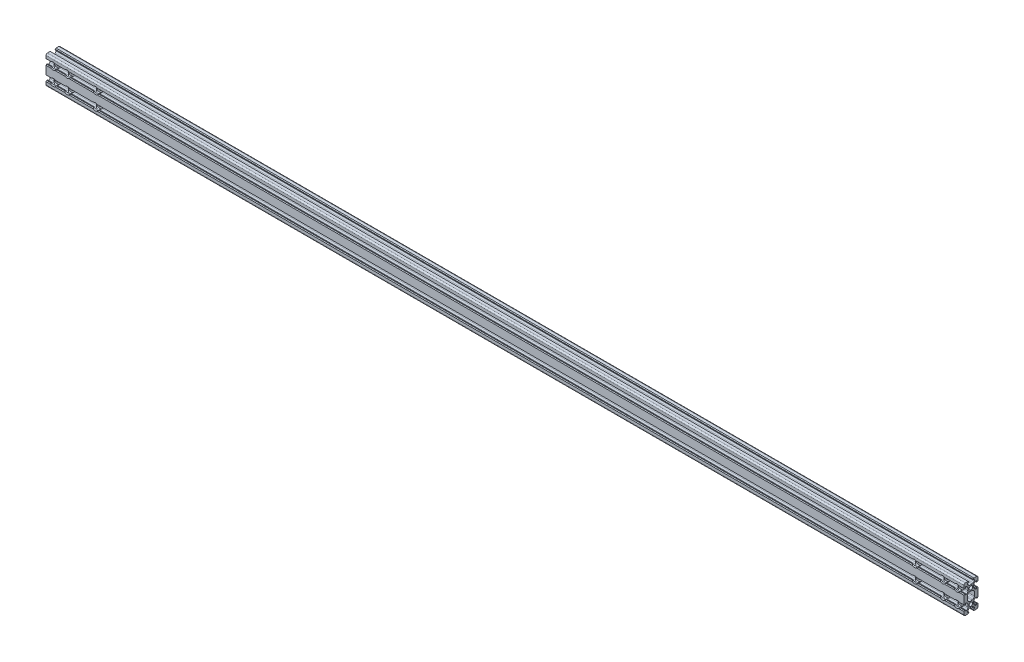
SolidWorks part; units mm, degrees
ref_plane "Front Plane" through (0, 0, 0) normal (0, 0, 1) x (1, 0, 0)
ref_plane "Top Plane" through (0, 0, 0) normal (0, 1, 0) x (1, 0, 0)
ref_plane "Right Plane" through (0, 0, 0) normal (1, 0, 0) x (0, 0, -1)
sketch "Sketch1" plane through (0, 0, 0) normal (1, 0, 0) x (0, 0, -1)
  line B0 (6.9, 38) -> (5, 38)
  line B1 (19, 6.9) -> (20, 5.9)
  line B2 (14.4142, 15.8284) -> (13.1236, 14.5379)
  line B3 (20, 14.1) -> (19, 13.1)
  line B4 (15.8284, 5.5858) -> (14.5379, 6.8764)
  line B5 (17.2426, 5) -> (18, 5)
  line B6 (18, 6.9) -> (18, 5)
  line B7 (17.2426, 15) -> (18, 15)
  line B8 (8.2906, 13.9521) -> (11.7094, 13.9521)
  line B9 (18, 15) -> (18, 13.1)
  line B10 (18, 13.1) -> (19, 13.1)
  line B11 (18, 6.9) -> (19, 6.9)
  line B12 (13.9521, 11.7094) -> (13.9521, 8.2906)
  line B13 (6.8764, 14.5379) -> (5.5858, 15.8284)
  line B14 (20, 5.9) -> (20, 2)
  line B15 (14.5379, 13.1236) -> (15.8284, 14.4142)
  line B16 (6.9, 1) -> (5.9, 0)
  line B17 (18, 0) -> (14.1, 0)
  line B18 (14.1, 0) -> (13.1, 1)
  line B19 (5.5858, 4.1716) -> (6.8764, 5.4621)
  line B20 (5, 2.7574) -> (5, 2)
  line B21 (6.9, 2) -> (5, 2)
  line B22 (15, 2.7574) -> (15, 2)
  line B23 (15, 2) -> (13.1, 2)
  line B24 (13.1, 2) -> (13.1, 1)
  line B25 (6.9, 2) -> (6.9, 1)
  line B26 (11.7094, 6.0479) -> (8.2906, 6.0479)
  line B27 (5.9, 0) -> (2, 0)
  line B28 (13.1236, 5.4621) -> (14.4142, 4.1716)
  line B29 (1, 13.1) -> (0, 14.1)
  line B30 (0, 2) -> (0, 5.9)
  line B31 (0, 5.9) -> (1, 6.9)
  line B32 (4.1716, 14.4142) -> (5.4621, 13.1236)
  line B33 (2.7574, 15) -> (2, 15)
  line B34 (2, 13.1) -> (2, 15)
  line B35 (2.7574, 5) -> (2, 5)
  line B36 (2, 5) -> (2, 6.9)
  line B37 (2, 6.9) -> (1, 6.9)
  line B38 (2, 13.1) -> (1, 13.1)
  line B39 (6.0479, 8.2906) -> (6.0479, 11.7094)
  line B40 (5.4621, 6.8764) -> (4.1716, 5.5858)
  line B41 (19, 26.9) -> (20, 25.9)
  line B42 (15, 38) -> (13.1, 38)
  line B43 (14.1, 40) -> (13.1, 39)
  line B44 (14.4142, 35.8284) -> (13.1236, 34.5379)
  line B45 (18, 35) -> (18, 33.1)
  line B46 (6.9, 38) -> (6.9, 39)
  line B47 (18, 40) -> (14.1, 40)
  line B48 (5.9, 40) -> (2, 40)
  line B49 (0, 25.9) -> (1, 26.9)
  line B50 (17.2426, 25) -> (18, 25)
  line B51 (5, 37.2426) -> (5, 38)
  line B52 (18, 26.9) -> (19, 26.9)
  line B53 (13.1, 38) -> (13.1, 39)
  line B54 (2, 26.9) -> (1, 26.9)
  line B55 (20, 34.1) -> (19, 33.1)
  line B56 (5, 22.7574) -> (5, 17.2426)
  line B57 (20, 34.1) -> (20, 38)
  line B58 (0, 38) -> (0, 34.1)
  line B59 (13.1236, 25.4621) -> (14.4142, 24.1716)
  line B60 (2, 25) -> (2, 26.9)
  line B61 (6.0479, 28.2906) -> (6.0479, 31.7094)
  line B62 (18, 33.1) -> (19, 33.1)
  line B63 (15, 37.2426) -> (15, 38)
  line B64 (2, 33.1) -> (2, 35)
  line B65 (18, 26.9) -> (18, 25)
  line B66 (11.7094, 26.0479) -> (8.2906, 26.0479)
  line B67 (17.2426, 35) -> (18, 35)
  line B68 (20, 25.9) -> (20, 14.1)
  line B69 (1, 33.1) -> (0, 34.1)
  line B70 (14.5379, 33.1236) -> (15.8284, 34.4142)
  line B71 (4.1716, 34.4142) -> (5.4621, 33.1236)
  line B72 (13.9521, 31.7094) -> (13.9521, 28.2906)
  line B73 (2.7574, 35) -> (2, 35)
  line B74 (8.2906, 33.9521) -> (11.7094, 33.9521)
  line B75 (6.9, 39) -> (5.9, 40)
  line B76 (5.4621, 26.8764) -> (4.1716, 25.5858)
  line B77 (0, 14.1) -> (0, 25.9)
  line B78 (5.5858, 24.1716) -> (6.8764, 25.4621)
  line B79 (15.8284, 25.5858) -> (14.5379, 26.8764)
  line B80 (6.8764, 34.5379) -> (5.5858, 35.8284)
  line B81 (15, 22.7574) -> (15, 17.2426)
  line B82 (2.7574, 25) -> (2, 25)
  line B83 (2, 33.1) -> (1, 33.1)
  circle B84 centre (10, 10) radius 2.5
  arc B85 (5.4621, 13.1236) -> (6.0479, 11.7094) centre (4.0479, 11.7094) cw
  arc B86 (4.1716, 14.4142) -> (2.7574, 15) centre (2.7574, 13) ccw
  arc B87 (5, 17.2426) -> (5.5858, 15.8284) centre (7, 17.2426) ccw
  arc B88 (15, 17.2426) -> (14.4142, 15.8284) centre (13, 17.2426) cw
  arc B89 (17.2426, 15) -> (15.8284, 14.4142) centre (17.2426, 13) ccw
  arc B90 (15.8284, 5.5858) -> (17.2426, 5) centre (17.2426, 7) ccw
  arc B91 (15, 2.7574) -> (14.4142, 4.1716) centre (13, 2.7574) ccw
  arc B92 (5.5858, 4.1716) -> (5, 2.7574) centre (7, 2.7574) ccw
  arc B93 (2.7574, 5) -> (4.1716, 5.5858) centre (2.7574, 7) ccw
  arc B94 (6.0479, 8.2906) -> (5.4621, 6.8764) centre (4.0479, 8.2906) cw
  arc B95 (6.8764, 5.4621) -> (8.2906, 6.0479) centre (8.2906, 4.0479) cw
  arc B96 (11.7094, 6.0479) -> (13.1236, 5.4621) centre (11.7094, 4.0479) cw
  arc B97 (14.5379, 6.8764) -> (13.9521, 8.2906) centre (15.9521, 8.2906) cw
  arc B98 (13.9521, 11.7094) -> (14.5379, 13.1236) centre (15.9521, 11.7094) cw
  arc B99 (11.7094, 13.9521) -> (13.1236, 14.5379) centre (11.7094, 15.9521) ccw
  arc B100 (8.2906, 13.9521) -> (6.8764, 14.5379) centre (8.2906, 15.9521) cw
  arc B101 (2, 0) -> (0, 2) centre (2, 2) cw
  arc B102 (20, 2) -> (18, 0) centre (18, 2) cw
  arc B103 (11.7094, 26.0479) -> (13.1236, 25.4621) centre (11.7094, 24.0479) cw
  arc B104 (13.9521, 31.7094) -> (14.5379, 33.1236) centre (15.9521, 31.7094) cw
  arc B105 (14.5379, 26.8764) -> (13.9521, 28.2906) centre (15.9521, 28.2906) cw
  arc B106 (5.5858, 24.1716) -> (5, 22.7574) centre (7, 22.7574) ccw
  arc B107 (5, 37.2426) -> (5.5858, 35.8284) centre (7, 37.2426) ccw
  arc B108 (11.7094, 33.9521) -> (13.1236, 34.5379) centre (11.7094, 35.9521) ccw
  arc B109 (15, 22.7574) -> (14.4142, 24.1716) centre (13, 22.7574) ccw
  arc B110 (2.7574, 25) -> (4.1716, 25.5858) centre (2.7574, 27) ccw
  arc B111 (15, 37.2426) -> (14.4142, 35.8284) centre (13, 37.2426) cw
  circle B112 centre (10, 30) radius 2.5
  arc B113 (8.2906, 33.9521) -> (6.8764, 34.5379) centre (8.2906, 35.9521) cw
  arc B114 (6.0479, 28.2906) -> (5.4621, 26.8764) centre (4.0479, 28.2906) cw
  arc B115 (6.8764, 25.4621) -> (8.2906, 26.0479) centre (8.2906, 24.0479) cw
  arc B116 (4.1716, 34.4142) -> (2.7574, 35) centre (2.7574, 33) ccw
  arc B117 (15.8284, 25.5858) -> (17.2426, 25) centre (17.2426, 27) ccw
  arc B118 (5.4621, 33.1236) -> (6.0479, 31.7094) centre (4.0479, 31.7094) cw
  arc B119 (2, 40) -> (0, 38) centre (2, 38) ccw
  arc B120 (17.2426, 35) -> (15.8284, 34.4142) centre (17.2426, 33) ccw
  arc B121 (20, 38) -> (18, 40) centre (18, 38) ccw
sketch_block_instance "2040-1"
sketch_block "2040" parameters "D1"=2, "D2"=2
extrude "Boss-Extrude1" add sketch "Sketch1" along normal blind 1300
sketch "Sketch2" plane through (0, 0, 0) normal (0, 0, 1) x (1, 0, 0)
  line L0 (1300, 30) -> (1290, 30) construction
  line L1 (1300, 31.7094) -> (1300, 28.2906) construction
  line L2 (1300, 10) -> (1290, 10) construction
  line L3 (1300, 11.7094) -> (1300, 8.2906) construction
  line L4 (1290, 30) -> (1270, 30) construction
  line L5 (1270, 30) -> (1250, 30) construction
  line L6 (1290, 10) -> (1270, 10) construction
  line L7 (1270, 10) -> (1250, 10) construction
  line L8 (1250, 30) -> (1230, 30) construction
  line L9 (1250, 10) -> (1230, 10) construction
  line L10 (650, 88.0521) -> (650, -38.9467) construction
  line L11 (50, 10) -> (70, 10) construction
  line L12 (50, 30) -> (70, 30) construction
  line L13 (30, 10) -> (50, 10) construction
  line L14 (10, 10) -> (30, 10) construction
  line L15 (30, 30) -> (50, 30) construction
  line L16 (10, 30) -> (30, 30) construction
  line L17 (0, 10) -> (10, 10) construction
  line L18 (0, 30) -> (10, 30) construction
  circle A0 centre (1290, 30) radius 2.5
  circle A1 centre (1270, 30) radius 2.5
  circle A2 centre (1230, 30) radius 2.5
  circle A3 centre (1290, 10) radius 2.5
  circle A4 centre (1270, 10) radius 2.5
  circle A5 centre (1230, 10) radius 2.5
  circle A6 centre (70, 10) radius 2.5
  circle A7 centre (30, 10) radius 2.5
  circle A8 centre (10, 10) radius 2.5
  circle A9 centre (70, 30) radius 2.5
  circle A10 centre (30, 30) radius 2.5
  circle A11 centre (10, 30) radius 2.5
extrude "Cut-Extrude1" cut sketch "Sketch2" against normal through all
sketch "Sketch3" plane through (0, 0, 0) normal (0, 0, 1) x (1, 0, 0)
  line L0 (650, 88.0521) -> (650, -38.9467) construction
  line L1 (650, 88.0521) -> (650, -38.9467) construction
  circle A0 centre (1290, 30) radius 5
  circle A1 centre (1270, 30) radius 5
  circle A2 centre (1230, 30) radius 5
  circle A3 centre (1230, 10) radius 5
  circle A4 centre (1270, 10) radius 5
  circle A5 centre (1290, 10) radius 5
  circle A6 centre (10, 10) radius 5
  circle A7 centre (30, 10) radius 5
  circle A8 centre (70, 10) radius 5
  circle A9 centre (70, 30) radius 5
  circle A10 centre (30, 30) radius 5
  circle A11 centre (10, 30) radius 5
extrude "Cut-Extrude2" cut sketch "Sketch3" against normal up to surface (6.0479 mm away) up to face at (1296.0811, 30, -6.0479)
